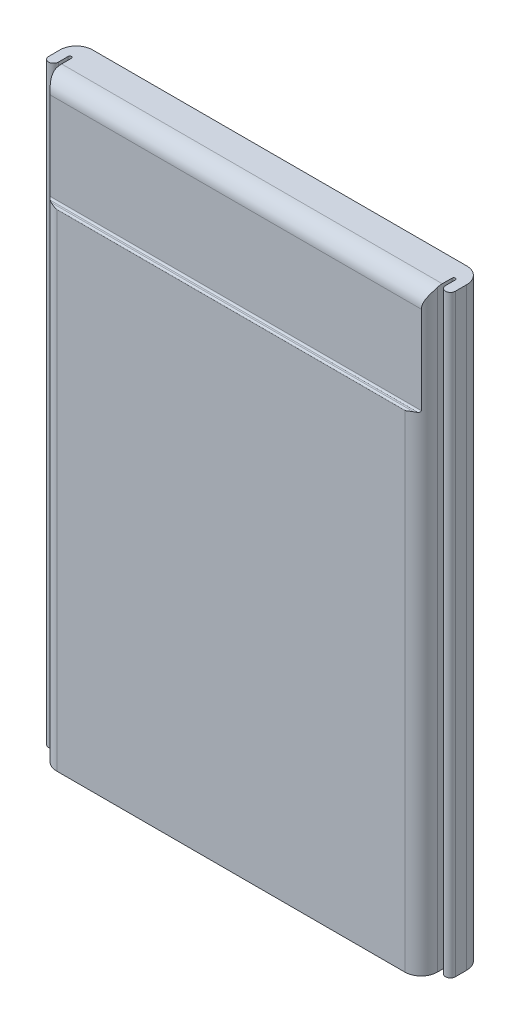
SolidWorks part; units mm, degrees
ref_plane "Front" through (0, 0, 0) normal (0, 0, 1) x (1, 0, 0)
ref_plane "Top" through (0, 0, 0) normal (0, 1, 0) x (1, 0, 0)
ref_plane "Right" through (0, 0, 0) normal (1, 0, 0) x (0, 0, -1)
sketch "Эскиз1" plane through (0, 0, 0) normal (0, 1, 0) x (1, 0, 0)
  line L0 (-11.5, 0) -> (11.5, 0)
  line L1 (-10.7, -3) -> (10.7, -3)
  line L2 (-12.5, -1) -> (-12.5, -1.7)
  line L3 (12.5, -1) -> (12.5, -1.7)
  line L4 (-11.7, -2) -> (-11.7, -1.1)
  line L5 (11.7, -1.1) -> (11.7, -2)
  line L6 (11.9, -1.7) -> (11.9, -1.1)
  line L7 (-11.9, -1.7) -> (-11.9, -1.1)
  arc A0 (-11.5, 0) -> (-12.5, -1) centre (-11.5, -1) ccw
  arc A1 (11.5, 0) -> (12.5, -1) centre (11.5, -1) cw
  arc A2 (-11.7, -2) -> (-10.7, -3) centre (-10.7, -2) ccw
  arc A3 (11.7, -2) -> (10.7, -3) centre (10.7, -2) cw
  arc A4 (12.5, -1.7) -> (11.9, -1.7) centre (12.2, -1.7) cw
  arc A5 (11.7, -1.1) -> (11.9, -1.1) centre (11.8, -1.1) cw
  arc A6 (-12.5, -1.7) -> (-11.9, -1.7) centre (-12.2, -1.7) ccw
  arc A7 (-11.7, -1.1) -> (-11.9, -1.1) centre (-11.8, -1.1) ccw
  point P20 (11.8, -1)
  point P21 (12.2, -2)
  point P27 (-11.8, -1)
  point P28 (-12.2, -2)
  dimension "D1" = 25
  dimension "D3" = 1
  dimension "D4" = 1
  dimension "D5" = 0.3
  dimension "D6" = 0.1
  dimension "D2" = 3
extrude "Бобышка-Вытянуть1" add sketch "Эскиз1" along normal mid plane 36.5
sketch "Эскиз2" plane through (0, 0, 0) normal (1, 0, 0) x (0, 0, -1)
  line L0 (-2.7, 17.25) -> (-2.7, 11.85)
  line L1 (-2.8, 11.75) -> (-2.9, 11.75)
  line L2 (-3, 18.25) -> (-3, 11.65)
  line L3 (-3, 18.25) -> (-3, -18.25) construction
  line L6 (-3, 18.25) -> (-1.7, 18.25)
  line L7 (0, 18.25) -> (-1, 18.25) construction
  arc A0 (-2.7, 11.85) -> (-2.8, 11.75) centre (-2.8, 11.85) cw
  arc A1 (-2.9, 11.75) -> (-3, 11.65) centre (-2.9, 11.65) ccw
  arc A2 (-1.7, 18.25) -> (-2.7, 17.25) centre (-1.7, 17.25) ccw
  dimension "D1" = 0.1
  dimension "D4" = 1
  dimension "D2" = 2.7
  dimension "D3" = 6.5
extrude "Вырез-Вытянуть1" cut sketch "Эскиз2" against normal up to next and the other way up to next
